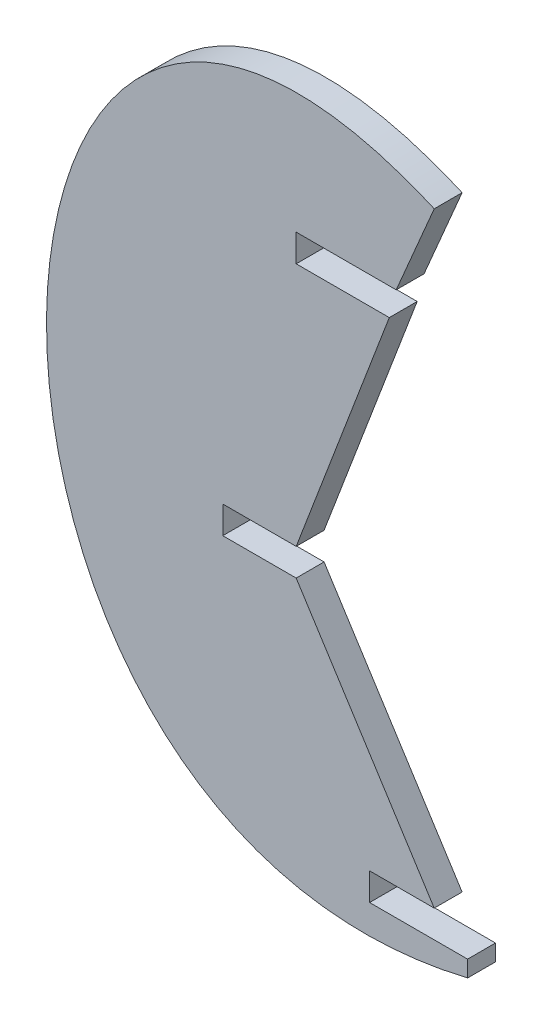
SolidWorks part; units mm, degrees
ref_plane "Piano frontale" through (0, 0, 0) normal (0, 0, 1) x (1, 0, 0)
ref_plane "Piano superiore" through (0, 0, 0) normal (0, 1, 0) x (1, 0, 0)
ref_plane "Piano destro" through (0, 0, 0) normal (1, 0, 0) x (0, 0, -1)
sketch "Model" plane through (0, 0, 0) normal (0, 0, 1) x (1, 0, 0)
  line L0 (-5, 0.09) -> (-5, -3.2541)
  line L1 (-25.0225, 0.09) -> (-5, 0.09)
  line L2 (-25.0225, 5.7) -> (-25.0225, 0.09)
  line L3 (-11.8183, 5.7) -> (-25.0225, 5.7)
  line L4 (-40.0225, 50.0086) -> (-11.8183, 5.7)
  line L5 (-55.0225, 50) -> (-40.0225, 50.0086)
  line L6 (-55.0225, 55.61) -> (-55.0225, 50)
  line L7 (-40.0225, 55.61) -> (-55.0225, 55.61)
  line L8 (-20.9989, 105.61) -> (-40.0225, 55.61)
  line L9 (-40.0225, 105.61) -> (-20.9989, 105.61)
  line L10 (-40.0225, 111.22) -> (-40.0225, 105.61)
  line L11 (-19.5847, 111.22) -> (-40.0225, 111.22)
  line L12 (-11.8183, 129.4488) -> (-19.5847, 111.22)
  spline S0 degree 3 poles (-5, -3.2541) (-122.0399, -31.2646) (-115.1307, 174.5423) (-11.8183, 129.4488) knots 0 0 0 0 1 1 1 1
  point P14 (-18.4204, 5.7)
  dimension "D1" = 5.61
  dimension "D2" = 5.61
  dimension "D4" = 50
  dimension "D5" = 44.3209
  dimension "D3" = 5.61
  dimension "D6" = 3.3441
extrude "Estrusione-Estrusione1" add sketch "Model" along normal blind 5.7 contours L8 L7 L6 L5 L4 L3 L2 L1 L0 S0 L12 L11 L10 L9
equation "\"k\"= 0.045mm'kerf"
equation "\"w\"= 30mm'circle width"
equation "\"m\"= 5.7mm'material thickness"
equation "\"jhf\"= \"m\" - 2 * \"k\"'female joint height"
equation "\"jhm\"= \"m\" + 2 * \"k\"'male joint height"
equation "\"d\"= 50mm'circle diameter"
equation "\"d2\"= \"d\" + 30mm"
equation "\"d3\"= \"d2\" + 30mm"
equation "\"id\"= 50mm'internal circle distance"
equation "\"D1@Model\"=\"m\"- 2 * \"k\""
equation "\"D2@Model\"=\"m\"- 2 *\"k\""
equation "\"D4@Model\"=\"id\""
equation "\"D3@Model\"=\"m\"- 2 * \"k\" "
